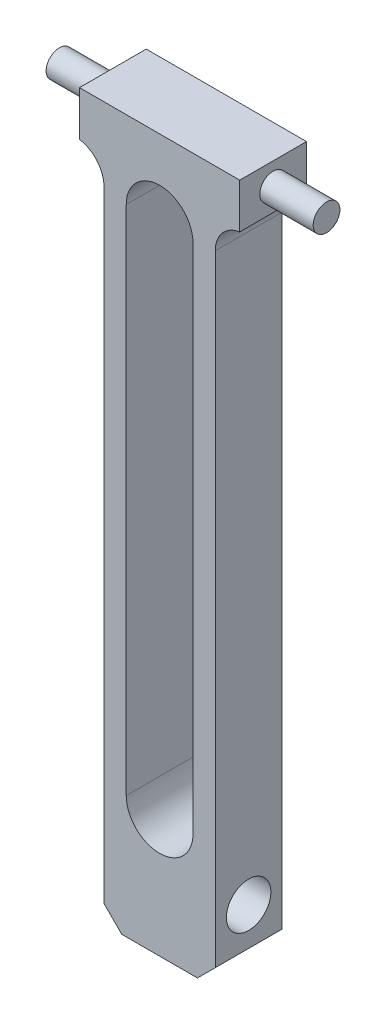
SolidWorks part; units mm, degrees
ref_plane "Ebene vorne" through (0, 0, 0) normal (0, 0, 1) x (1, 0, 0)
ref_plane "Ebene oben" through (0, 0, 0) normal (0, 1, 0) x (1, 0, 0)
ref_plane "Ebene rechts" through (0, 0, 0) normal (1, 0, 0) x (0, 0, -1)
sketch "Skizze1" plane through (0, 0, 0) normal (0, 0, 1) x (1, 0, 0)
  line L0 (-8.75, 75) -> (-3.25, 75)
  line L1 (2, 0) -> (10.5, 0)
  line L2 (0, 2) -> (0, 71.75)
  line L3 (15.75, 75) -> (21.25, 75)
  line L4 (12.5, 2) -> (12.5, 71.75)
  line L5 (-8.75, 75) -> (-8.75, 80)
  line L6 (10.5, 0) -> (12.5, 2)
  line L7 (-8.75, 80) -> (21.25, 80)
  line L8 (21.25, 80) -> (21.25, 75)
  line L9 (0, 2) -> (2, 0)
  arc A0 (15.75, 75) -> (12.5, 71.75) centre (15.75, 71.75) ccw
  arc A1 (-3.25, 75) -> (0, 71.75) centre (-3.25, 71.75) cw
  point P0 (0, 0)
  point P3 (12.5, 0)
  dimension "D5" = 3.25
  dimension "D1" = 12.5
  dimension "D2" = 30
  dimension "D3" = 8.75
  dimension "D4" = 5
  dimension "D7" = 5
  dimension "D8" = 80
extrude "Aufsatz-Linear austragen1" add sketch "Skizze1" along normal blind 7.5
sketch "Skizze2" plane through (0, 0, 7.5) normal (0, 0, 1) x (1, 0, 0)
  line L1 (6.25, 71.25) -> (6.25, 13.75) construction
  line L2 (10, 71.25) -> (10, 13.75)
  line L3 (2.5, 71.25) -> (2.5, 13.75)
  line L4 (0, 71.75) -> (0, 2) construction
  line L6 (15.75, 75) -> (21.25, 75) construction
  arc A0 (10, 71.25) -> (2.5, 71.25) centre (6.25, 71.25) ccw
  arc A1 (2.5, 13.75) -> (10, 13.75) centre (6.25, 13.75) ccw
  point P2 (6.25, 42.5)
  dimension "D3" = 7.5
  dimension "D1" = 6.25
  dimension "D2" = 57.5
extrude "Schnitt-Linear austragen1" cut sketch "Skizze2" against normal blind 10
sketch "Skizze7" plane through (12.5, 0, 0) normal (1, 0, 0) x (0, 0, -1)
  line L0 (-7.5, 0) -> (0, 0) construction
  line L1 (0, 2) -> (0, 71.75) construction
  circle A0 centre (-3.75, 6.25) radius 2.5
  dimension "D1" = 5
  dimension "D2" = 6.25
  dimension "D3" = 3.75
extrude "Schnitt-Linear austragen4" cut sketch "Skizze7" against normal through all
hole_wizard "M4 Gewindebohrung1" positions "3D-Skizze2" profile "Skizze8" tap size "M4" standard "DIN"
sketch3d "3D-Skizze2"
  line L0 (12.5, 0, 7.5) -> (12.5, 0, 0) construction
  line L1 (2, 0, 7.5) -> (10.5, 0, 7.5) construction
  point P2 (6.25, 0, 3.75)
  dimension "D2" = 6.25
  dimension "D3" = 3.75
sketch "Skizze8" plane through (6.25, 0, 3.75) normal (1, 0, 0) x (0, 0, -1)
  line L0 (0, 0) -> (0, 8.4914)
  line L1 (0, 8.4914) -> (1.65, 7.5)
  line L2 (1.65, 7.5) -> (1.65, 0)
  line L5 (1.65, 0) -> (0, 0)
  line L10 (0, 8.4914) -> (-1.65, 7.5) construction
  line L11 (0, -6.35) -> (0, 107.95) construction
  dimension "Bohrerdurchmesser" = 3.3
  dimension "Bohrungstiefe" = 7.5
  dimension "Spitzenwinkel" = 118
cosmetic thread "Bohrungsgewinde1" parameters "D1"=4.3718, "D2"=4
sketch "Skizze9" plane through (21.25, 0, 0) normal (1, 0, 0) x (0, 0, -1)
  line L0 (-7.5, 80) -> (0, 80) construction
  line L1 (-7.5, 75) -> (-7.5, 80) construction
  circle A0 centre (-3.75, 77.5) radius 1.5
  dimension "D1" = 3
  dimension "D2" = 2.5
  dimension "D3" = 3.75
extrude "Schnitt-Linear austragen5" cut sketch "Skizze9" against normal blind 6 flip side to cut
sketch "Skizze10" plane through (-8.75, 0, 0) normal (-1, 0, 0) x (0, 0, 1)
  circle A0 centre (3.75, 77.5) radius 1.5
  circle A1 centre (3.75, 77.5) radius 1.5 construction
  dimension "D1" = 3
extrude "Schnitt-Linear austragen6" cut sketch "Skizze10" against normal blind 6 flip side to cut
